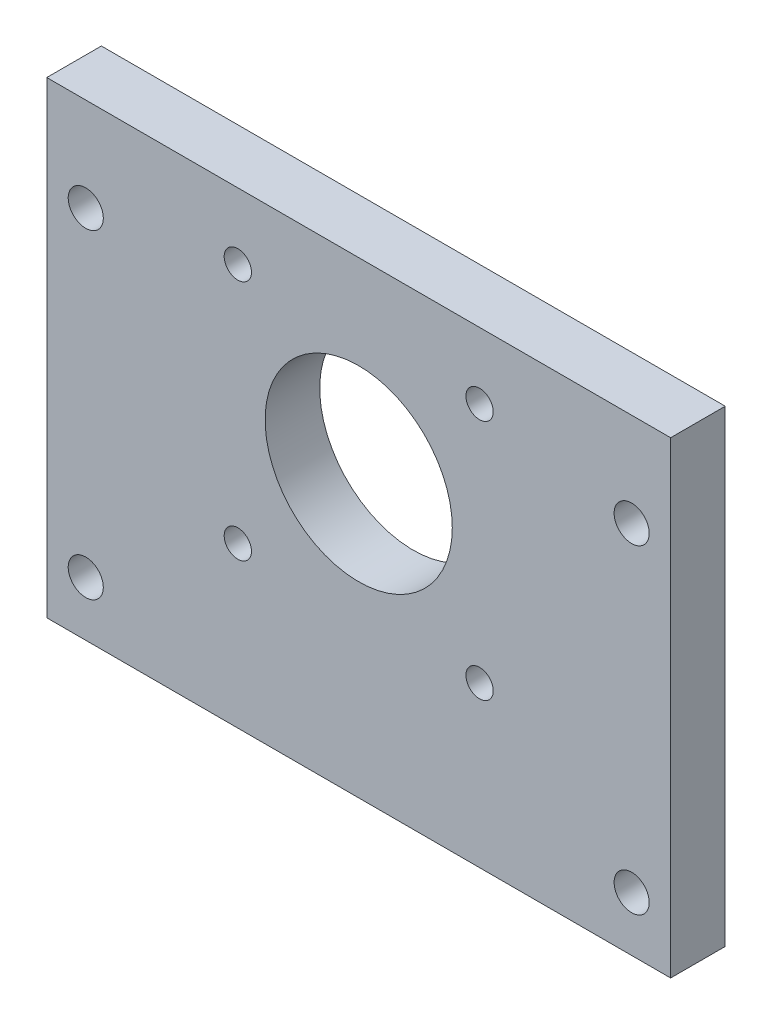
SolidWorks part; units mm, degrees
ref_plane "前视基准面" through (0, 0, 0) normal (0, 0, 1) x (1, 0, 0)
ref_plane "上视基准面" through (0, 0, 0) normal (0, 1, 0) x (1, 0, 0)
ref_plane "右视基准面" through (0, 0, 0) normal (1, 0, 0) x (0, 0, -1)
other "Configuration Table"
sketch "外形与孔位_z_motor_mount" plane through (0, 0, 0) normal (0, 0, 1) x (1, 0, 0)
  line L0 (0, 0) -> (80, 0)
  line L1 (80, 0) -> (80, 60)
  line L2 (80, 60) -> (0, 60)
  line L3 (0, 60) -> (0, 0)
  circle A0 centre (40, 36) radius 12
  circle A1 centre (24.5, 20.5) radius 1.75
  circle A2 centre (24.5, 51.5) radius 1.75
  circle A3 centre (55.5, 20.5) radius 1.75
  circle A4 centre (55.5, 51.5) radius 1.75
  circle A5 centre (5, 7) radius 2.25
  circle A6 centre (5, 48) radius 2.25
  circle A7 centre (75, 7) radius 2.25
  circle A8 centre (75, 48) radius 2.25
extrude "板厚_7mm" add sketch "外形与孔位_z_motor_mount" along normal blind 7
